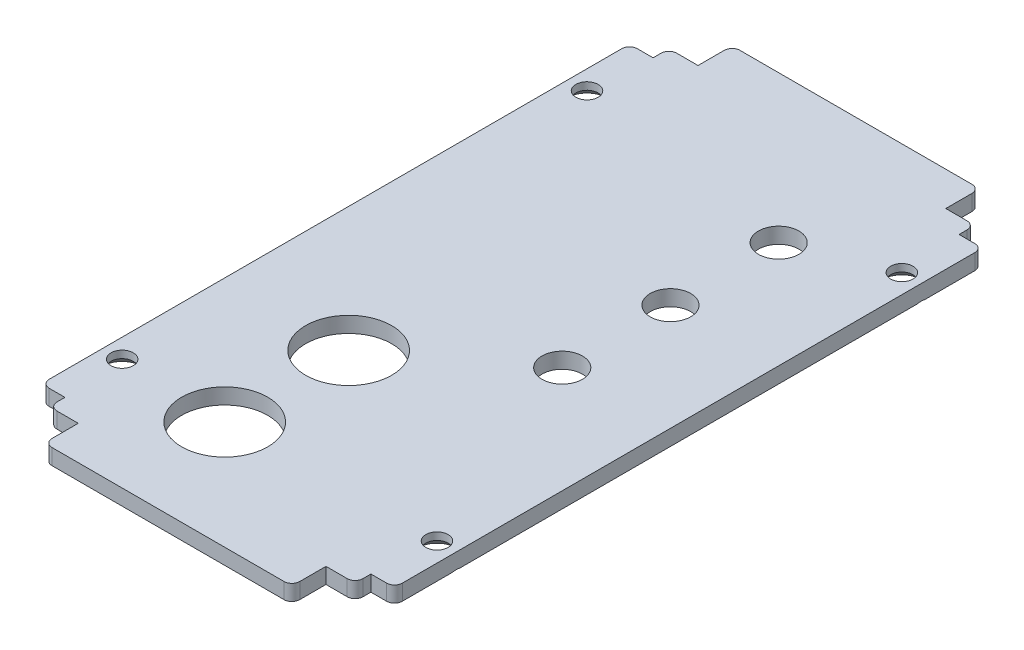
SolidWorks part; units mm, degrees
ref_plane "Front Plane" through (0, 0, 0) normal (0, 0, 1) x (1, 0, 0)
ref_plane "Top Plane" through (0, 0, 0) normal (0, 1, 0) x (1, 0, 0)
ref_plane "Right Plane" through (0, 0, 0) normal (1, 0, 0) x (0, 0, -1)
sketch "Sketch1" plane through (0, 0, 0) normal (0, 1, 0) x (1, 0, 0)
  line L1 (-30.3276, -64.2493) -> (30.3276, -64.2493)
  line L2 (-30.3276, -64.2493) -> (-30.3276, 64.2493)
  line L3 (-30.3276, 64.2493) -> (30.3276, 64.2493)
  line L4 (30.3276, -64.2493) -> (30.3276, 64.2493)
  line L5 (-30.3276, -64.2493) -> (30.3276, 64.2493) construction
  line L6 (-30.3276, 64.2493) -> (30.3276, -64.2493) construction
  point P0 (0, 0)
  dimension "D1" = 128.4986
  dimension "D2" = 60.6552
extrude "Boss-Extrude1" add sketch "Sketch1" along normal blind 2.54
sketch "Sketch2" plane through (0, 0, 0) normal (0, 1, 0) x (1, 0, 0)
  line L0 (25.4, 37.5031) -> (25.4, -37.5031) construction
  line L1 (22.86, 61.2521) -> (22.86, -61.2521) construction
  line L2 (-30.3276, -64.2493) -> (30.3276, -64.2493) construction
  line L3 (30.3276, -64.2493) -> (30.3276, 64.2493) construction
  line L4 (-30.3276, -49.2633) -> (30.3276, -49.2633) construction
  line L5 (-30.3276, 64.2493) -> (-30.3276, -64.2493) construction
  line L6 (30.3276, 64.2493) -> (-30.3276, 64.2493) construction
  line L7 (30.3276, -64.2493) -> (30.3276, 64.2493) construction
  line L8 (-30.3276, -64.2493) -> (30.3276, -64.2493) construction
  line L9 (-17.78, -49.2633) -> (17.78, -49.2633)
  point P18 (0, -49.2633)
  point P21 (0, -49.2633)
  dimension "D1" = 26.7462
  dimension "D2" = 75.0062
  dimension "D3" = 4.9276
  dimension "D4" = 7.4676
  dimension "D5" = 122.5042
  dimension "D6" = 2.9972
  dimension "D7" = 14.986
  dimension "D8" = 17.78
hole_wizard "CSK for M3 Flat Head Machine Screw1" positions "Sketch6" profile "Sketch5" countersink size "M3" standard "ANSI Metric" end condition through all
sketch "Sketch6" plane through (0, 0, 0) normal (0, -1, 0) x (-1, 0, 0)
  point P0 (-25.4, 37.5031)
  point P3 (-25.4, -37.5031)
sketch "Sketch5" plane through (25.4, 0, -37.5031) normal (1, 0, 0) x (0, 0, -1)
  line L0 (0, 0) -> (0, 2.54)
  line L1 (0, 2.54) -> (1.8, 2.54)
  line L2 (1.8, 2.54) -> (1.8, 1.35)
  line L3 (1.8, 1.35) -> (3.15, 0)
  line L5 (3.15, 0) -> (0, 0)
  line L6 (-1.8, 1.35) -> (-3.15, 0) construction
  line L11 (0, -6.35) -> (0, 107.95) construction
  dimension "Thru Hole Dia." = 3.6
  dimension "Thru Hole Depth" = 2.54
  dimension "Near C'Sink Dia." = 6.3
  dimension "Near C'Sink Angle" = 90
hole_wizard "M2.5 Clearance Slot1" positions "Sketch53" profile "Sketch9" size "M2.5" standard "ANSI Metric"
sketch "Sketch53" plane through (0, 0, 0) normal (0, -1, 0) x (-1, 0, 0)
  line L0 (-22.36, 61.2521) -> (-23.36, 61.2521) construction
  point P0 (-22.86, 61.2521)
  point P3 (-22.86, -61.2521)
  point P6 (-17.78, -49.2633)
  point P9 (0, -49.2633)
  point P12 (17.78, -49.2633)
  dimension "D1" = 1
sketch "Sketch9" plane through (22.86, 0, -61.2521) normal (1, 0, 0) x (0, 0, -1)
  line L0 (0, 0) -> (0, 2.54)
  line L1 (0, 2.54) -> (1.45, 2.54)
  line L2 (1.45, 2.54) -> (1.45, 0)
  line L5 (1.45, 0) -> (0, 0)
  line L11 (0, -6.35) -> (0, 107.95) construction
  dimension "Thru Hole Dia." = 2.9
  dimension "Thru Hole Depth" = 2.54
sketch "Sketch12" plane through (0, 2.54, 0) normal (0, 1, 0) x (1, 0, 0)
  line L1 (28.4861, 50.1523) -> (-28.4861, 50.1523) construction
  line L2 (28.4861, 50.1523) -> (28.4861, -50.1523) construction
  line L3 (28.4861, -50.1523) -> (-28.4861, -50.1523) construction
  line L4 (-28.4861, 50.1523) -> (-28.4861, -50.1523) construction
  line L6 (18.3261, 50.1523) -> (18.3261, -50.1523)
  dimension "D1" = 56.9722
  dimension "D2" = 100.3046
  dimension "D3" = 50.1523
  dimension "D4" = 28.4861
  dimension "D5" = 10.16
ref_plane "Plane1" through (18.3261, 0, 0) normal (1, 0, 0) x (0, 0, 1)
mirror "Mirror1" about plane through (0, 0, 0) normal (1, 0, 0) of "M2.5 Clearance Slot1", "CSK for M3 Flat Head Machine Screw1"
sketch "Main hole sketch" plane through (0, 0, 0) normal (0, -1, 0) x (1, 0, 0)
  line L0 (-16.3576, 32.7988) -> (-16.3576, -35.0012)
  line L2 (-2.0701, -21.3012) -> (12.2174, -21.3012)
  line L3 (30.3276, -64.2493) -> (-30.3276, -64.2493) construction
  line L4 (-30.3276, 0) -> (30.3276, 0) construction
  line L5 (-30.3276, -64.2493) -> (-30.3276, 64.2493) construction
  line L6 (30.3276, 64.2493) -> (30.3276, -64.2493) construction
  line L7 (-2.0701, -35.0012) -> (12.2174, -35.0012)
  line L8 (-16.3576, 32.7988) -> (-2.0701, 32.7988)
  line L9 (-2.0701, 32.7988) -> (12.2174, 32.7988)
  line L11 (-9.7536, 17.0888) -> (12.2174, 17.0888)
  line L13 (-11.938, -9.7312) -> (-11.938, -2.7312)
  line L14 (-11.938, -2.7312) -> (-11.938, 4.2688)
  circle A0 centre (5.0736, -2.7312) radius 11.43 construction
  point P0 (-9.7536, 17.0888)
  point P19 (-16.3576, -1.1012)
  point P20 (-16.3576, -21.3012)
  point P35 (-11.938, -9.7312)
  dimension "D12" = 22.86
  dimension "D1" = 13.97
  dimension "D2" = 67.8
  dimension "D3" = 6.604
  dimension "D4" = 15.71
  dimension "D5" = 13.7
  dimension "D6" = 14.2875
  dimension "D7" = 14.2875
  dimension "D8" = 14.2875
  dimension "D9" = 11.57
  dimension "D10" = 4.4196
  dimension "D11" = 7
  dimension "D13" = 14.2875
  dimension "D14" = 0
  dimension "D15" = 0
  dimension "D16" = 29.2481
sketch "Sketch54" plane through (0, 0, 0) normal (0, -1, 0) x (1, 0, 0)
  line L1 (-28.4861, -55.499) -> (28.4861, -55.499)
  line L2 (-28.4861, -55.499) -> (-28.4861, 55.499)
  line L3 (-28.4861, 55.499) -> (28.4861, 55.499)
  line L4 (28.4861, -55.499) -> (28.4861, 55.499)
  line L5 (-28.4861, -55.499) -> (28.4861, 55.499) construction
  line L6 (-28.4861, 55.499) -> (28.4861, -55.499) construction
  line L7 (-35.838, 72.6338) -> (37.9132, 72.6338)
  line L8 (-35.838, 72.6338) -> (-35.838, -70.5585)
  line L9 (-35.838, -70.5585) -> (37.9132, -70.5585)
  line L10 (37.9132, 72.6338) -> (37.9132, -70.5585)
  point P0 (0, 0)
  dimension "D1" = 56.9722
  dimension "D2" = 110.998
extrude "Cut-Extrude1" cut sketch "Sketch54" against normal blind 2.54
sketch "Sketch55" plane through (0, 0, 0) normal (0, -1, 0) x (1, 0, 0)
  line L1 (28.4861, 55.499) -> (19.9861, 55.499)
  line L2 (28.4861, 55.499) -> (28.4861, 49.9999)
  line L3 (28.4861, 49.9999) -> (19.9861, 49.9999)
  line L4 (19.9861, 55.499) -> (19.9861, 49.9999)
  line L5 (28.4861, 49.9999) -> (24.6861, 49.9999)
  line L6 (28.4861, 49.9999) -> (28.4861, 47.4499)
  line L7 (28.4861, 47.4499) -> (24.6861, 47.4499)
  line L8 (24.6861, 49.9999) -> (24.6861, 47.4499)
  line M6 (28.4861, 38.1344) -> (28.4861, 55.499)
  line M7 (28.4861, 55.499) -> (-28.4861, 55.499)
  dimension "D1" = 5.4991
  dimension "D2" = 8.5
  dimension "D3" = 3.8
  dimension "D4" = 2.55
extrude "Cut-Extrude2" cut sketch "Sketch55" against normal blind 2.54 contours L4 L3 M7 M6 | L3 L8 L7 M6
mirror "Mirror4" about plane through (0, 0, 0) normal (1, 0, 0) of "Cut-Extrude2"
sketch "Sketch56" plane through (0, 0, 0) normal (0, -1, 0) x (1, 0, 0)
  line L0 (-8.3566, 38) -> (-8.3566, 18)
  line L1 (-30.3276, 64.2493) -> (-30.3276, -64.2493) construction
  line L2 (11.2776, 3.175) -> (11.2776, -14.2875)
  line L3 (11.2776, -14.2875) -> (11.2776, -31.75)
  line L4 (30.3276, 64.2493) -> (30.3276, -64.2493) construction
  dimension "D1" = 21.971
  dimension "D2" = 18
  dimension "D3" = 20
  dimension "D4" = 17.4625
  dimension "D5" = 19.05
  dimension "D6" = 3.175
hole_wizard "1/2 Clearance Hole1" positions "Sketch59" profile "Sketch58" hole size "1/2" standard "ANSI Inch"
sketch "Sketch59" plane through (0, 0, 0) normal (0, -1, 0) x (-1, 0, 0)
  point P0 (8.3566, -18)
  point P3 (8.3566, -38)
sketch "Sketch58" plane through (-8.3566, 0, 18) normal (1, 0, 0) x (0, 0, -1)
  line L0 (0, 0) -> (0, 2.54)
  line L1 (0, 2.54) -> (6.9456, 2.54)
  line L2 (6.9456, 2.54) -> (6.9456, 0)
  line L5 (6.9456, 0) -> (0, 0)
  line L11 (0, -6.35) -> (0, 107.95) construction
  dimension "Thru Hole Dia." = 13.8913
  dimension "Thru Hole Depth" = 2.54
hole_wizard "1/4 Clearance Hole1" positions "Sketch62" profile "Sketch61" hole size "1/4" standard "ANSI Inch"
sketch "Sketch62" plane through (0, 0, 0) normal (0, -1, 0) x (-1, 0, 0)
  point P0 (-11.2776, -3.175)
  point P3 (-11.2776, 14.2875)
  point P6 (-11.2776, 31.75)
sketch "Sketch61" plane through (11.2776, 0, 3.175) normal (1, 0, 0) x (0, 0, -1)
  line L0 (0, 0) -> (0, 2.54)
  line L1 (0, 2.54) -> (3.2639, 2.54)
  line L2 (3.2639, 2.54) -> (3.2639, 0)
  line L5 (3.2639, 0) -> (0, 0)
  line L11 (0, -6.35) -> (0, 107.95) construction
  dimension "Thru Hole Dia." = 6.5278
  dimension "Thru Hole Depth" = 2.54
fillet "Fillet1" radius 1.27 12 edges at (19.9861, 1.27, 55.499) (28.4861, 1.27, 47.4499) (24.6861, 1.27, 49.9999) (19.9861, 1.27, -55.499) (24.6861, 1.27, -49.9999) (28.4861, 1.27, -47.4499) (-19.9861, 1.27, 55.499) (-24.6861, 1.27, 49.9999) (-28.4861, 1.27, 47.4499) (-19.9861, 1.27, -55.499) (-28.4861, 1.27, -47.4499) (-24.6861, 1.27, -49.9999)
